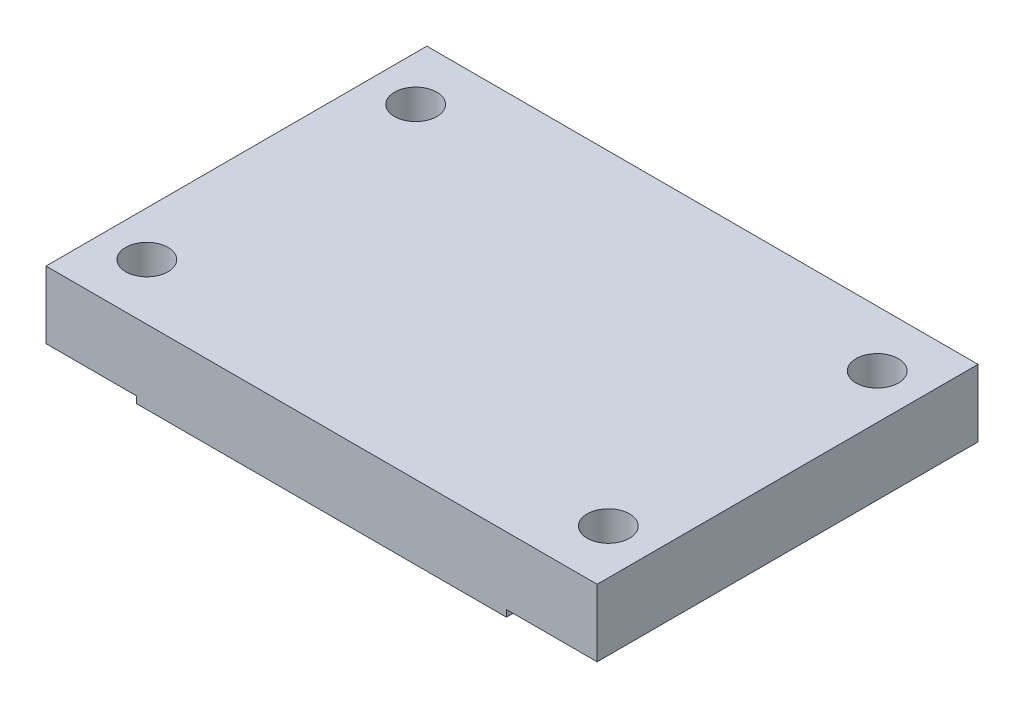
SolidWorks part; units mm, degrees
ref_plane "Front Plane" through (0, 0, 0) normal (0, 0, 1) x (1, 0, 0)
ref_plane "Top Plane" through (0, 0, 0) normal (0, 1, 0) x (1, 0, 0)
ref_plane "Right Plane" through (0, 0, 0) normal (1, 0, 0) x (0, 0, -1)
sketch "Sketch1" plane through (0, 0, 0) normal (0, 1, 0) x (1, 0, 0)
  line L0 (0, 0) -> (0, 15.24) construction
  line L1 (-31.242, -21.5037) -> (31.242, -21.5037)
  line L2 (-31.242, -21.5037) -> (-31.242, 21.6763)
  line L3 (-31.242, 21.6763) -> (31.242, 21.6763)
  line L4 (31.242, -21.5037) -> (31.242, 21.6763)
  circle A0 centre (-26.162, 15.3263) radius 2.4003
  circle A1 centre (-26.162, -15.1537) radius 2.4003
  circle A2 centre (26.162, -15.1537) radius 2.4003
  circle A3 centre (26.162, 15.3263) radius 2.4003
  point P0 (0, 0)
  point P16 (0, 0)
  dimension "D3" = 4.8006
  dimension "D4" = 4.8006
  dimension "D5" = 5.08
  dimension "D6" = 5.08
  dimension "D7" = 30.48
  dimension "D8" = 6.35
  dimension "D9" = 30.48
  dimension "D1" = 62.484
  dimension "D2" = 43.18
extrude "Boss-Extrude1" add sketch "Sketch1" along normal blind 7.62
sketch "Sketch2" plane through (0, 0, 0) normal (0, -1, 0) x (1, 0, 0)
  line L0 (-31.242, 21.5037) -> (31.242, 21.5037) construction
  line L1 (-20.955, -21.5037) -> (20.955, -21.5037)
  line L2 (-20.955, -21.5037) -> (-20.955, 21.5037)
  line L3 (-20.955, 21.5037) -> (20.955, 21.5037)
  line L4 (20.955, -21.5037) -> (20.955, 21.5037)
  line L5 (-20.955, -21.5037) -> (20.955, 21.5037) construction
  line L6 (-20.955, 21.5037) -> (20.955, -21.5037) construction
  point P0 (0, 0)
  dimension "D1" = 41.91
extrude "Boss-Extrude2" add sketch "Sketch2" along normal blind 0.762
